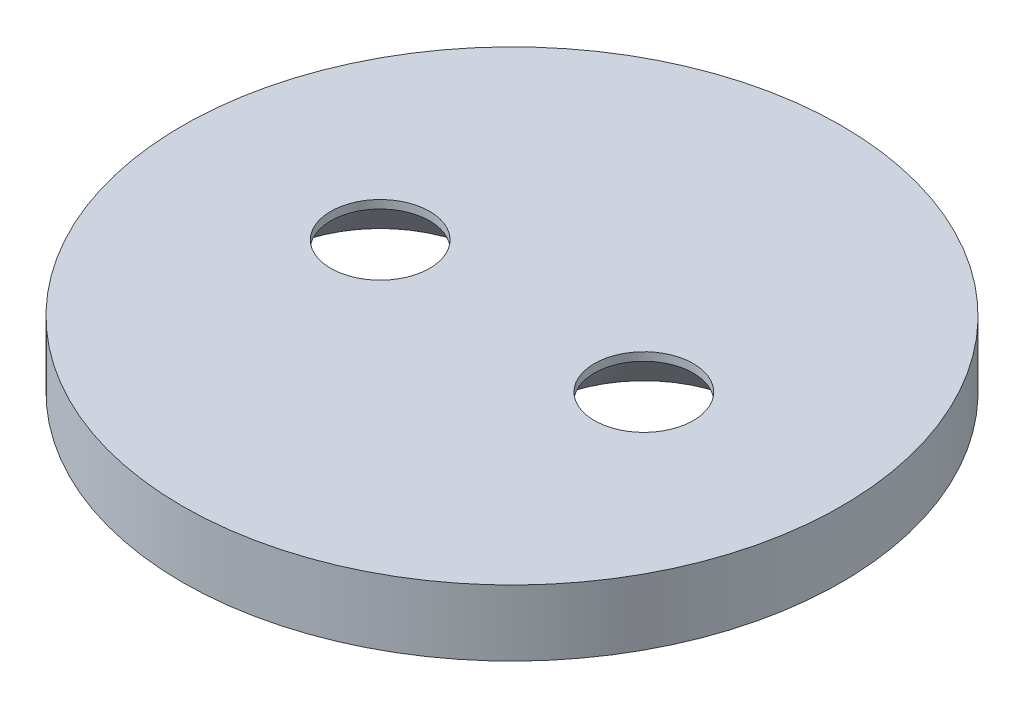
SolidWorks part; units mm, degrees
ref_plane "前视基准面" through (0, 0, 0) normal (0, 0, 1) x (1, 0, 0)
ref_plane "上视基准面" through (0, 0, 0) normal (0, 1, 0) x (1, 0, 0)
ref_plane "右视基准面" through (0, 0, 0) normal (1, 0, 0) x (0, 0, -1)
sketch "草图1" plane through (0, 0, 0) normal (0, 1, 0) x (1, 0, 0)
  circle A0 centre (0, 0) radius 10
  dimension "D1" = 20
extrude "凸台-拉伸1" add sketch "草图1" along normal blind 2
sketch "草图2" plane through (0, 0, 0) normal (0, -1, 0) x (1, 0, 0)
  line L0 (-4, 0) -> (4, 0) construction
  line L2 (1.1, 0) -> (-1.1, 0) construction
  point P1 (4, 0)
  point P3 (-4, 0)
  point P7 (0, 0)
  dimension "D1" = 8
hole_wizard "孔2" positions "草图2" profile "草图4" legacy
sketch "草图4" plane through (4, 0, 0) normal (1, 0, 0) x (0, 0, -1)
  line L0 (0, 0) -> (0, 2)
  line L1 (0, 2) -> (1.5, 2)
  line L2 (1.5, 2) -> (1.5, 1.75)
  line L3 (1.5, 1.75) -> (3.25, 0)
  line L4 (3.25, 0) -> (0, 0)
  line L5 (0, -6.4453) -> (0, 115.525) construction
  line L6 (-1.5, 1.75) -> (-3.25, 0) construction
  dimension "直径" = 3
  dimension "深度" = 2
  dimension "锥坑角度" = 90
  dimension "锥坑直径" = 6.5
